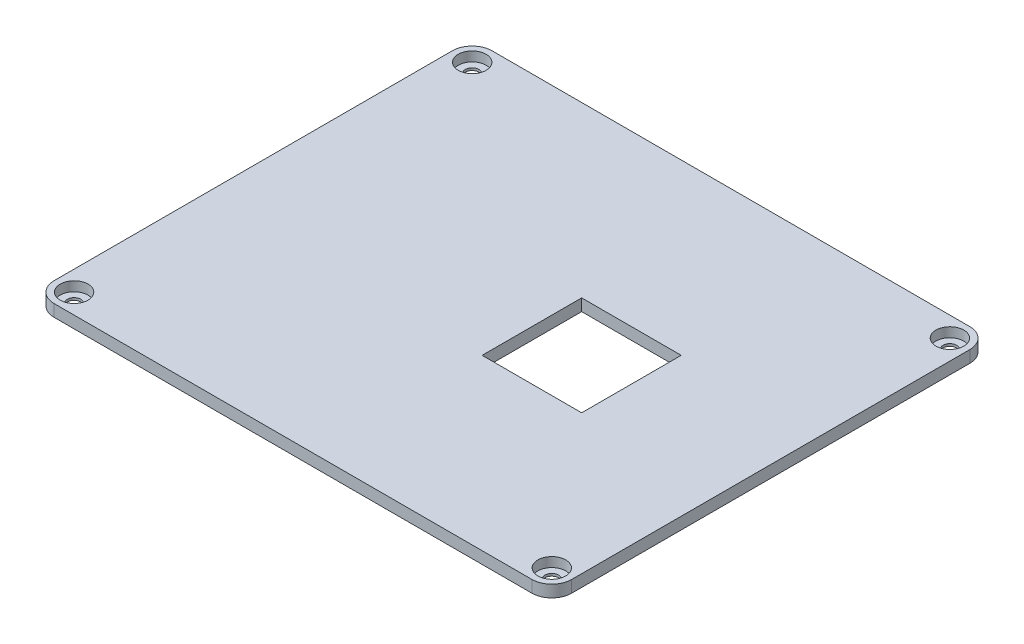
SolidWorks part; units mm, degrees
ref_plane "Front Plane" through (0, 0, 0) normal (0, 0, 1) x (1, 0, 0)
ref_plane "Top Plane" through (0, 0, 0) normal (0, 1, 0) x (1, 0, 0)
ref_plane "Right Plane" through (0, 0, 0) normal (1, 0, 0) x (0, 0, -1)
sketch "Sketch1" plane through (0, 0, 0) normal (0, 1, 0) x (1, 0, 0)
  line L1 (0, 0) -> (130, 0)
  line L2 (0, 0) -> (0, 110)
  line L3 (0, 110) -> (130, 110)
  line L4 (130, 0) -> (130, 110)
  dimension "D1" = 110
  dimension "D2" = 130
extrude "Boss-Extrude1" add sketch "Sketch1" along normal blind 3
hole_wizard "CBORE for M3 Pan Head Machine Screw1" positions "Sketch9" profile "Sketch8" counterbore size "M3" standard "ANSI Metric"
sketch "Sketch9" plane through (0, 3, 0) normal (0, 1, 0) x (1, 0, 0)
  line L0 (130, 110) -> (0, 110) construction
  line L1 (0, 110) -> (0, 0) construction
  line L2 (130, 0) -> (130, 110) construction
  line L3 (0, 0) -> (130, 0) construction
  point P0 (5, 105)
  point P2 (125, 105)
  point P4 (125, 5)
  point P6 (5, 5)
  dimension "D1" = 5
  dimension "D2" = 5
  dimension "D3" = 5
  dimension "D4" = 5
  dimension "D5" = 5
  dimension "D6" = 5
  dimension "D7" = 5
  dimension "D8" = 5
sketch "Sketch8" plane through (5, 3, -105) normal (1, 0, 0) x (0, 0, 1)
  line L0 (0, 0) -> (0, 8.0215)
  line L1 (0, 8.0215) -> (1.7, 7)
  line L2 (1.7, 7) -> (1.7, 2.4)
  line L3 (1.7, 2.4) -> (3.5, 2.4)
  line L4 (3.5, 2.4) -> (3.5, 0)
  line L5 (3.5, 0) -> (0, 0)
  line L10 (0, 8.0215) -> (-1.7, 7) construction
  line L11 (0, -6.35) -> (0, 107.95) construction
  dimension "Hole Dia." = 3.4
  dimension "Hole Depth" = 7
  dimension "C'Bore Dia." = 7
  dimension "C'Bore Depth" = 2.4
  dimension "Drill Angle" = 118
sketch "Sketch10" plane through (0, 3, 0) normal (0, 1, 0) x (1, 0, 0)
  line L2 (95, 67.5) -> (70, 67.5)
  line L3 (95, 67.5) -> (95, 42.5)
  line L4 (95, 42.5) -> (70, 42.5)
  line L5 (70, 67.5) -> (70, 42.5)
  line L6 (106.8035, 0) -> (106.8035, 110) construction
  line L7 (0, 0) -> (130, 0) construction
  line L8 (130, 110) -> (0, 110) construction
  line L9 (106.8035, 110) -> (106.8035, 55) construction
  line L10 (106.8035, 55) -> (126.9142, 55) construction
  line L11 (126.9142, 55) -> (-78.2244, 55) construction
  line L13 (130, 0) -> (130, 110) construction
  dimension "D1" = 25
  dimension "D2" = 25
  dimension "D3" = 42.5
  dimension "D4" = 35
extrude "Cut-Extrude1" cut sketch "Sketch10" against normal blind 5
fillet "Fillet1" radius 5 4 edges at (0, 1.5, -110) (0, 1.5, 0) (130, 1.5, -110) (130, 1.5, 0)
